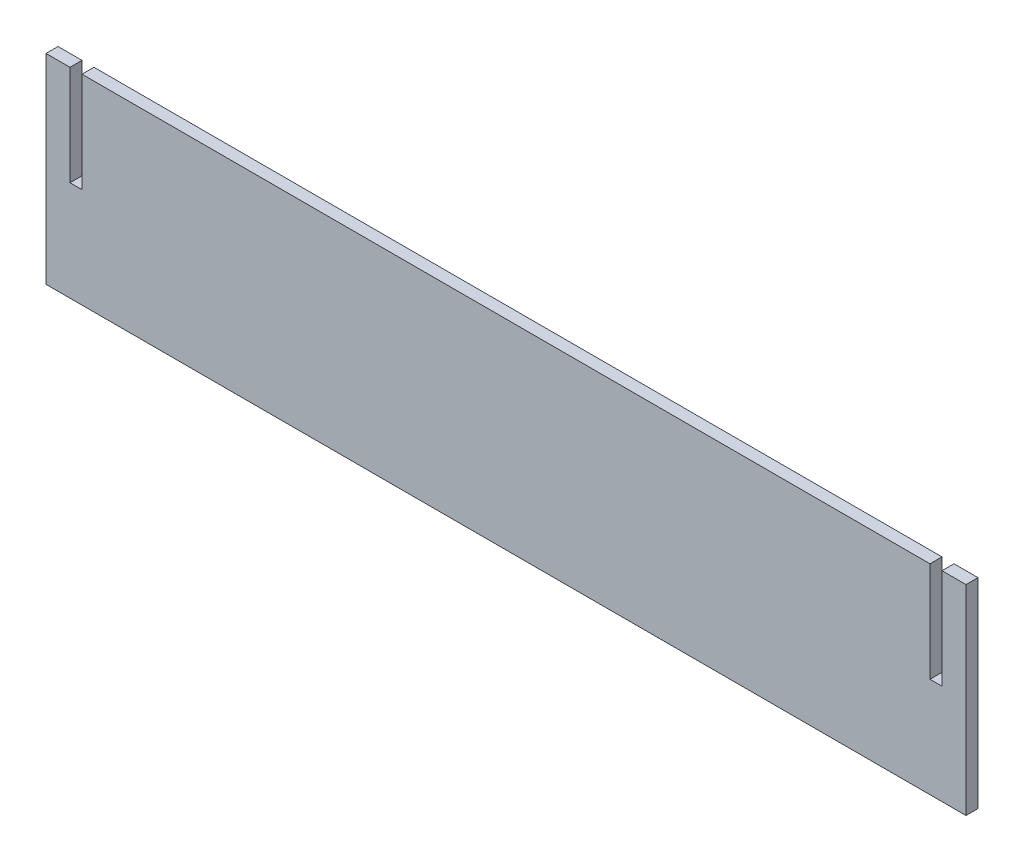
SolidWorks part; units mm, degrees
ref_plane "Plan de face" through (0, 0, 0) normal (0, 0, 1) x (1, 0, 0)
ref_plane "Plan de dessus" through (0, 0, 0) normal (0, 1, 0) x (1, 0, 0)
ref_plane "Plan de droite" through (0, 0, 0) normal (1, 0, 0) x (0, 0, -1)
sketch "Esquisse1" plane through (0, 0, 0) normal (0, 0, 1) x (1, 0, 0)
  line L0 (-109, 25) -> (-109, 0)
  line L1 (-115, 25) -> (-109, 25)
  line L2 (-115, 25) -> (-115, -25)
  line L3 (-115, -25) -> (115, -25)
  line L4 (115, 25) -> (115, -25)
  line L5 (-109, 0) -> (-106, 0)
  line L6 (-106, 0) -> (-106, 25)
  line L7 (-106, 25) -> (106, 25)
  line L8 (0, -55) -> (0, 55) construction
  line L9 (109, 0) -> (106, 0)
  line L10 (109, 25) -> (109, 0)
  line L11 (106, 0) -> (106, 25)
  line L12 (109, 25) -> (115, 25)
  point P5 (115, 0)
  dimension "D1" = 230
  dimension "D2" = 50
  dimension "D3" = 3
  dimension "D4" = 25
  dimension "D5" = 106
extrude "Boss.-Extru.1" add sketch "Esquisse1" along normal blind 3
